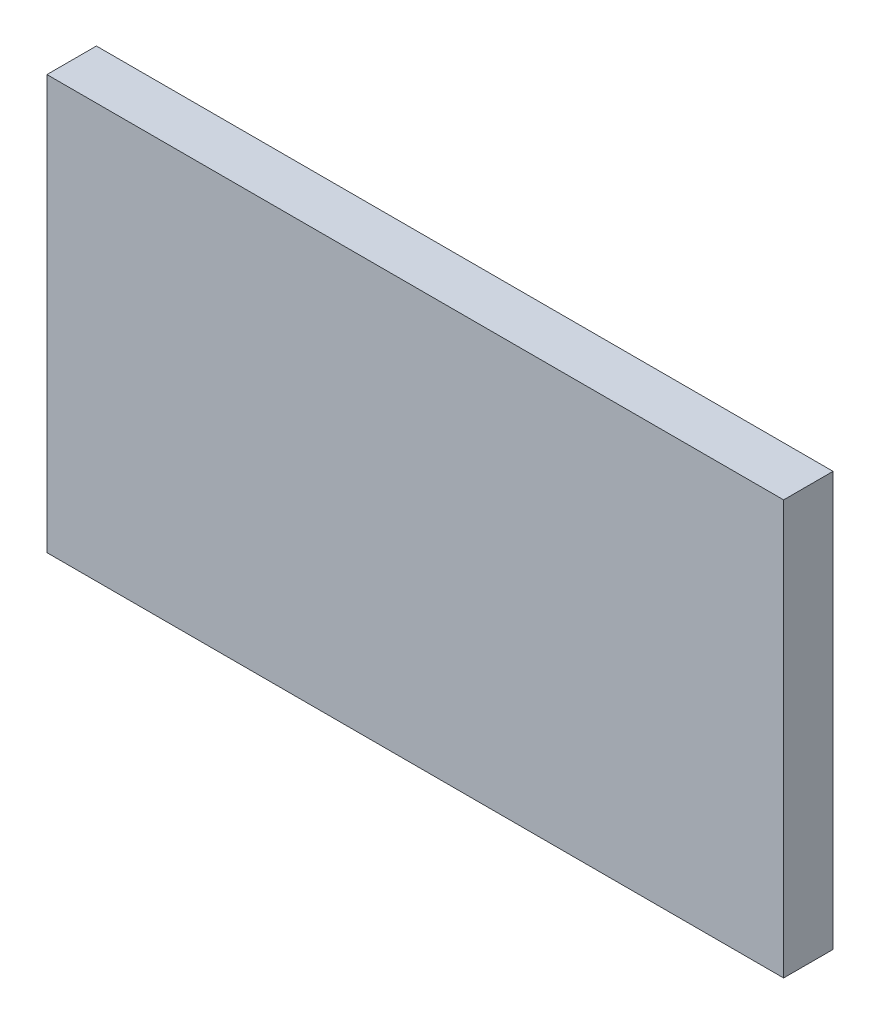
SolidWorks part; units mm, degrees
ref_plane "Front Plane" through (0, 0, 0) normal (0, 0, 1) x (1, 0, 0)
ref_plane "Top Plane" through (0, 0, 0) normal (0, 1, 0) x (1, 0, 0)
ref_plane "Right Plane" through (0, 0, 0) normal (1, 0, 0) x (0, 0, -1)
sketch "Sketch1" plane through (0, 0, 0) normal (0, 0, 1) x (1, 0, 0)
  line L1 (298, -167.5) -> (-298, -167.5)
  line L2 (298, -167.5) -> (298, 167.5)
  line L3 (298, 167.5) -> (-298, 167.5)
  line L4 (-298, -167.5) -> (-298, 167.5)
  line L5 (298, -167.5) -> (-298, 167.5) construction
  line L6 (298, 167.5) -> (-298, -167.5) construction
  point P0 (0, 0)
  dimension "D1" = 596
  dimension "D2" = 335
extrude "Boss-Extrude1" add sketch "Sketch1" along normal blind 40
